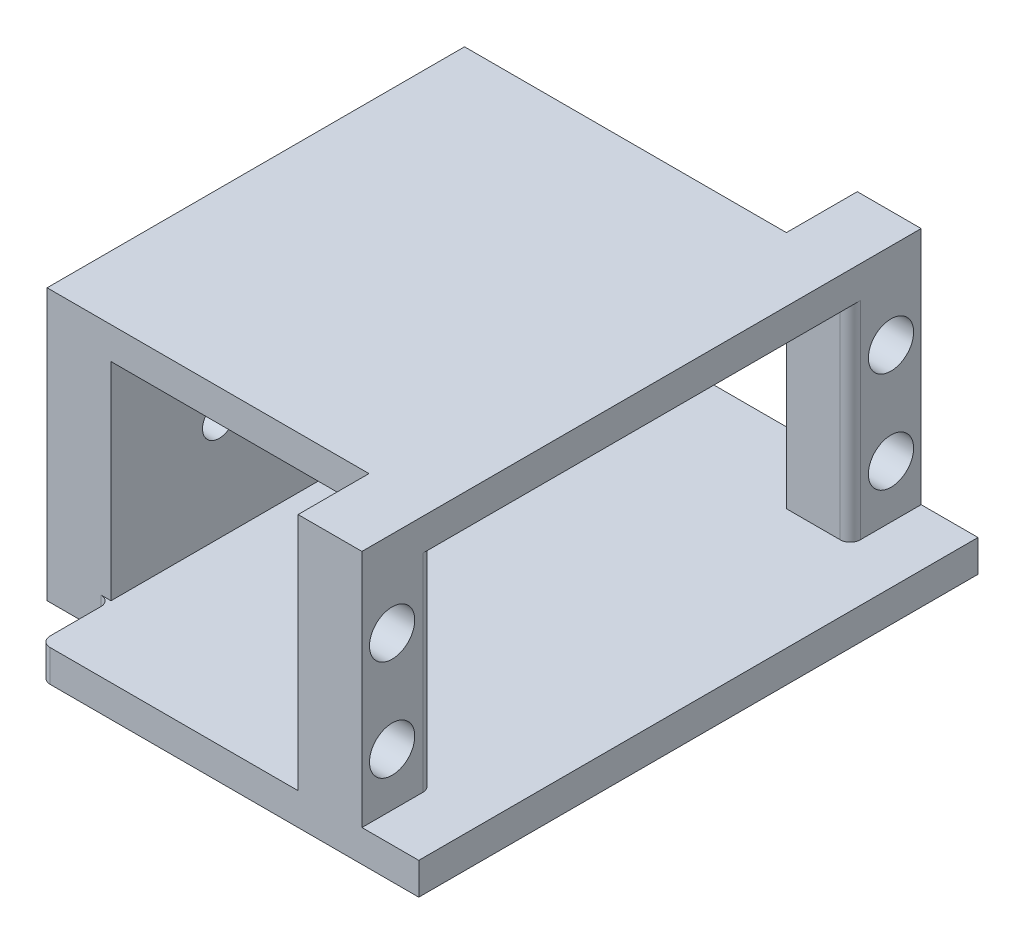
SolidWorks part; units mm, degrees
ref_plane "Front Plane" through (0, 0, 0) normal (0, 0, 1) x (1, 0, 0)
ref_plane "Top Plane" through (0, 0, 0) normal (0, 1, 0) x (1, 0, 0)
ref_plane "Right Plane" through (0, 0, 0) normal (1, 0, 0) x (0, 0, -1)
sketch "Sketch1" plane through (0, 0, 0) normal (0, 1, 0) x (1, 0, 0)
  line L1 (-22, 27.8) -> (22, 27.8)
  line L2 (-22, 27.8) -> (-22, -27.8)
  line L3 (-22, -27.8) -> (22, -27.8)
  line L4 (22, 27.8) -> (22, -27.8)
  line L5 (-22, 27.8) -> (22, -27.8) construction
  line L6 (-22, -27.8) -> (22, 27.8) construction
  point P0 (0, 0)
  dimension "D1" = 55.6
  dimension "D2" = 44
extrude "Boss-Extrude1" add sketch "Sketch1" along normal blind 3.175
sketch "Sketch2" plane through (0, 3.175, 0) normal (0, 1, 0) x (1, 0, 0)
  line L0 (-22, 27.8) -> (-22, -27.8) construction
  line L1 (-15.65, 20.75) -> (-22, 20.75)
  line L2 (-15.65, 20.75) -> (-15.65, -20.75)
  line L3 (-15.65, -20.75) -> (-22, -20.75)
  line L4 (-22, 20.75) -> (-22, -20.75)
  line L5 (-15.65, 20.75) -> (-22, -20.75) construction
  line L6 (-15.65, -20.75) -> (-22, 20.75) construction
  line L8 (-22, -27.8) -> (22, -27.8) construction
  line L9 (-22, 0) -> (65.8452, 0) construction
  line L12 (10, 27.8) -> (10, 20.75)
  line L13 (16.35, -27.8) -> (10, -27.8)
  line L14 (16.35, -27.8) -> (16.35, -20.75)
  line L15 (16.35, -20.75) -> (10, -20.75)
  line L16 (10, -27.8) -> (10, -20.75)
  line L17 (16.35, 20.75) -> (10, 20.75)
  line L18 (16.35, 27.8) -> (16.35, 20.75)
  line L19 (16.35, 27.8) -> (10, 27.8)
  line L27 (-3.55, 20.1) -> (16.25, 20.1) construction
  line L28 (-3.55, -20.1) -> (16.25, -20.1) construction
  line L30 (22, -27.8) -> (22, 27.8) construction
  point P0 (-18.825, 0)
  dimension "D1" = 6.35
  dimension "D4" = 6.35
  dimension "D6" = 7.05
  dimension "D9" = 41.5
  dimension "D2" = 41.5
  dimension "D3" = 0.65
  dimension "D7" = 0.65
  dimension "D5" = 5.65
extrude "Boss-Extrude2" add sketch "Sketch2" along normal blind 20.6
sketch "Sketch3" plane through (0, 23.775, 0) normal (0, 1, 0) x (1, 0, 0)
  line L0 (-22, 20.75) -> (10, 20.75)
  line L16 (16.35, -27.8) -> (10, -27.8)
  line L17 (10, -27.8) -> (10, -20.75)
  line L18 (10, -20.75) -> (-22, -20.75)
  line L19 (-22, -20.75) -> (-22, 20.75)
  line L20 (10, 20.75) -> (10, 27.8)
  line L21 (10, 27.8) -> (16.35, 27.8)
  line L22 (16.35, 27.8) -> (16.35, -27.8)
extrude "Boss-Extrude3" add sketch "Sketch3" along normal blind 3.175
sketch "Sketch5" plane through (16.35, 0, 0) normal (1, 0, 0) x (0, 0, -1)
  line L0 (-27.8, 26.95) -> (-27.8, 3.175) construction
  line L1 (-27.8, 3.175) -> (-20.75, 3.175) construction
  line L2 (0, 0) -> (0, 26.95) construction
  line L3 (-27.8, 26.95) -> (27.8, 26.95) construction
  circle A0 centre (-24.8, 8.425) radius 2.25
  circle A1 centre (-24.8, 18.425) radius 2.25
  circle A2 centre (24.8, 18.425) radius 2.25
  circle A3 centre (24.8, 8.425) radius 2.25
  point P13 (0, 0)
  dimension "D1" = 4.5
  dimension "D3" = 5.25
  dimension "D2" = 3
  dimension "D4" = 10
extrude "Cut-Extrude2" cut sketch "Sketch5" against normal up to surface (6.35 mm away) up to face at (10, 16.805, 23.57)
sketch "Sketch6" plane through (-22, 0, 0) normal (-1, 0, 0) x (0, 0, 1)
  circle A0 centre (10, 13.43) radius 1.65
  point P2 (0, 0)
  dimension "D1" = 3.3
extrude "Cut-Extrude3" cut sketch "Sketch6" against normal up to surface (6.35 mm away) contours A0 up to face at (-15.65, 13.475, 0)
fillet "Fillet1" radius 1 2 edges at (16.35, 13.475, 20.75) (16.35, 13.475, -20.75)
sketch "Sketch7" plane through (0, 3.175, 0) normal (0, 1, 0) x (1, 0, 0)
  line L1 (-22, -27.8) -> (-15.65, -27.8)
  line L2 (-22, -27.8) -> (-22, -20.75)
  line L3 (-22, -20.75) -> (-15.65, -20.75)
  line L4 (-15.65, -27.8) -> (-15.65, -20.75)
  line L5 (-22, 27.8) -> (-15.65, 27.8)
  line L6 (-22, 27.8) -> (-22, 20.75)
  line L7 (-22, 20.75) -> (-15.65, 20.75)
  line L8 (-15.65, 27.8) -> (-15.65, 20.75)
extrude "Cut-Extrude4" cut sketch "Sketch7" against normal up to surface (3.175 mm away) up to face at (0, 0, 0)
fillet "Fillet2" radius 1 4 edges at (-15.65, 1.5875, 27.8) (-15.65, 1.5875, 20.75) (-15.65, 1.5875, -20.75) (-15.65, 1.5875, -27.8)
equation "\"D4@Sketch2\"=\"D1@Sketch2\""
equation "\"D2@Sketch2\"=\"D9@Sketch2\""
